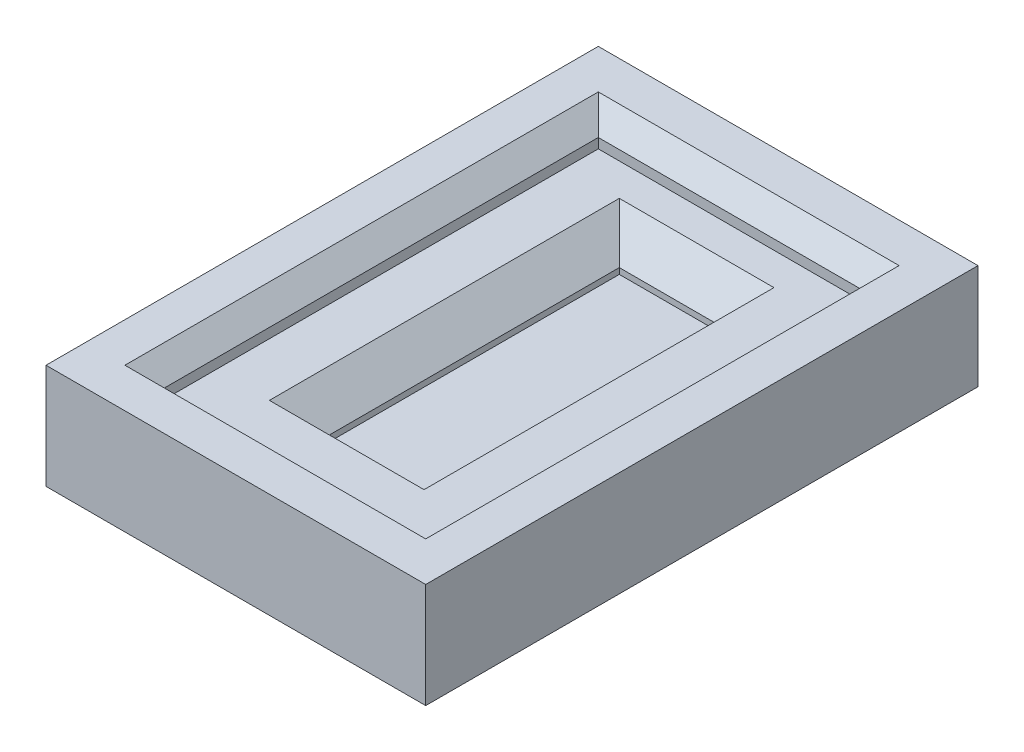
SolidWorks part; units mm, degrees
material "Грунт"
ref_plane "Спереди" through (0, 0, 0) normal (0, 0, 1) x (1, 0, 0)
ref_plane "Сверху" through (0, 0, 0) normal (0, 1, 0) x (1, 0, 0)
ref_plane "Справа" through (0, 0, 0) normal (1, 0, 0) x (0, 0, -1)
sketch "Эскиз1" plane through (0, 0, 0) normal (0, 0, 1) x (1, 0, 0)
  line L0 (-1200, -1660) -> (1200, -1660) construction
  line L1 (-1200, -1660) -> (1200, -1660)
  line L2 (1200, -1660) -> (1200, -1510) construction
  line L3 (1200, -1660) -> (1200, -1510)
  line L4 (-1200, -1660) -> (-1200, -1510) construction
  line L5 (-1200, -1660) -> (-1200, -1510)
  line L6 (1200, -1510) -> (1960, -750)
  line L7 (-3312.5, -750) -> (3312.5, -750) construction
  line L8 (1960, -750) -> (3312.5, -750)
  line L9 (3312.5, -750) -> (3312.5, -500)
  line L10 (3312.5, -500) -> (3812.5, 0)
  line L11 (3812.5, 0) -> (4812.5, 0)
  line L12 (4812.5, 0) -> (4812.5, -2660)
  line L13 (4812.5, -2660) -> (-4812.5, -2660)
  line L14 (-4812.5, -2660) -> (-4812.5, 0)
  line L15 (-4812.5, 0) -> (-3812.5, 0)
  line L16 (-3812.5, 0) -> (-3312.5, -500)
  line L17 (-3312.5, -500) -> (-3312.5, -750)
  line L18 (-3312.5, -750) -> (-3312.5, -500) construction
  line L19 (-3312.5, -750) -> (-1960, -750)
  line L20 (-1960, -750) -> (-1200, -1510)
  line L21 (2000, 0) -> (-2000, 0) construction
  dimension "D1" = 45
  dimension "D2" = 1000
  dimension "D3" = 1000
extrude "Бобышка-Вытянуть1" add sketch "Эскиз1" along normal offset from surface (7000 mm away) 1500
mirror "Зеркальное отражение2" about plane through (0, 0, 0) normal (0, 0, -1) of bodies 103
sketch "Эскиз3" plane through (-4812.5, 0, 0) normal (-1, 0, 0) x (0, 0, 1)
  line L0 (-3920, -1660) -> (3430, -1660) construction
  line L1 (-3920, -1660) -> (3430, -1660)
  line L2 (3430, -1660) -> (3430, -1510)
  line L3 (3430, -1510) -> (4190, -750)
  line L4 (7000, -750) -> (-7000, -750) construction
  line L5 (4190, -750) -> (5500, -750)
  line L6 (5500, -750) -> (5500, -500)
  line L7 (5500, -500) -> (6000, 0)
  line L8 (7000, 0) -> (-7000, 0) construction
  line L9 (6000, 0) -> (7000, 0)
  line L10 (7000, 0) -> (7000, -2660)
  line L11 (7000, -2660) -> (-7000, -2660)
  line L12 (-7000, -2660) -> (-7000, 0)
  line L13 (-7000, 0) -> (-6000, 0)
  line L14 (-6000, 0) -> (-5500, -500)
  line L15 (-5500, -500) -> (-5500, -750)
  line L16 (-5500, -750) -> (-4680, -750)
  line L17 (-4680, -750) -> (-3920, -1510)
  line L18 (-3920, -1510) -> (-3920, -1660)
  dimension "D1" = 45
extrude "Бобышка-Вытянуть2" add sketch "Эскиз3" against normal up to surface (9625 mm away) up to face at (4812.5, -1330, 0)
